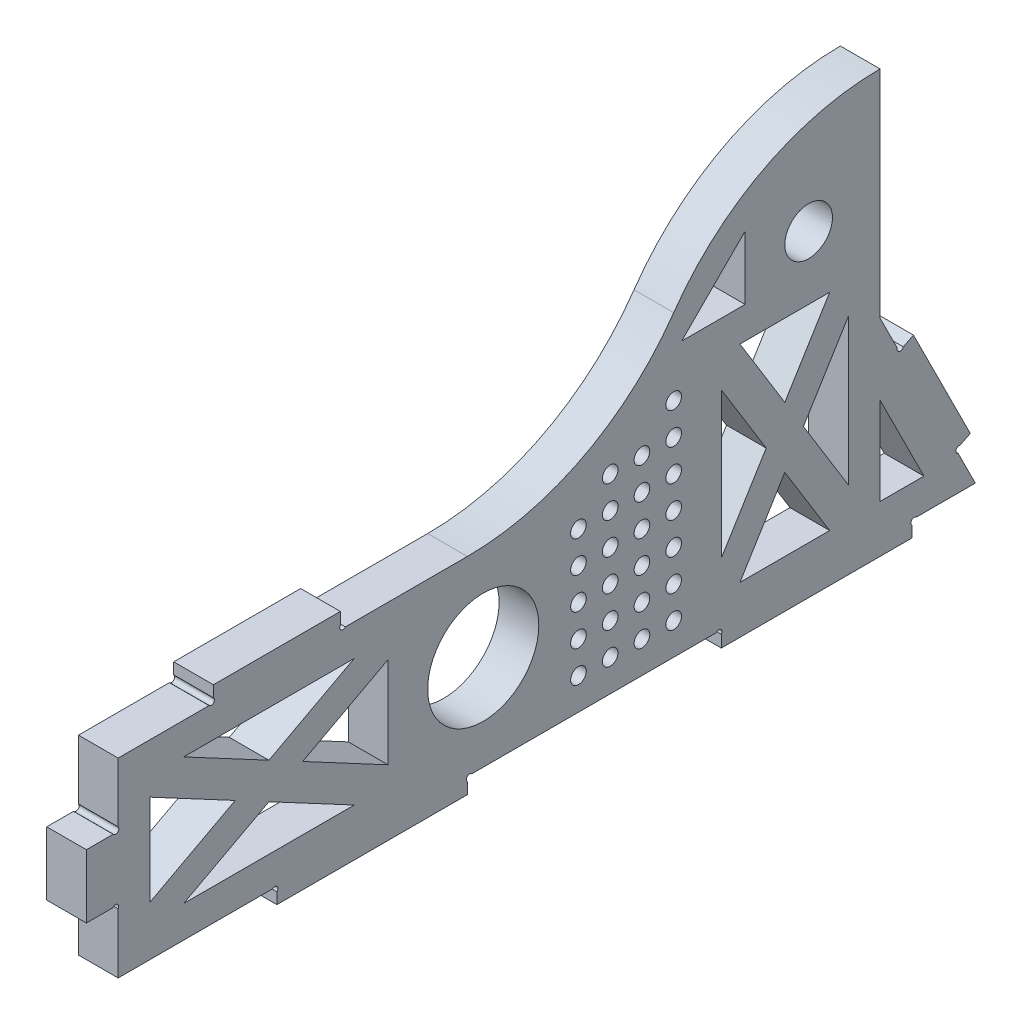
SolidWorks part; units mm, degrees
ref_plane "Front Plane" through (0, 0, 0) normal (0, 0, 1) x (1, 0, 0)
ref_plane "Top Plane" through (0, 0, 0) normal (0, 1, 0) x (1, 0, 0)
ref_plane "Right Plane" through (0, 0, 0) normal (1, 0, 0) x (0, 0, -1)
sketch "Sketch1" plane through (0, 0, 0) normal (1, 0, 0) x (0, 0, -1)
  line L0 (139.7, 38.1) -> (139.7, 124.46)
  line L1 (-177.8, -38.1) -> (177.8, -38.1)
  line L2 (-177.8, -38.1) -> (-177.8, 38.1)
  line L3 (-177.8, 38.1) -> (177.8, 38.1)
  line L4 (177.8, -38.1) -> (177.8, 38.1)
  line L5 (-177.8, -38.1) -> (177.8, 38.1) construction
  line L6 (-177.8, 38.1) -> (177.8, -38.1) construction
  line L7 (139.7, 124.46) -> (-25.4, 38.1)
  line L8 (139.7, 38.1) -> (177.8, -38.1)
  line L9 (-165.1, -38.1) -> (-165.1, 38.1)
  line L11 (-76.2, 38.1) -> (-127, 38.1)
  line L12 (-76.2, 38.1) -> (-76.2, 44.45)
  line L13 (-76.2, 44.45) -> (-127, 44.45)
  line L14 (-127, 38.1) -> (-127, 44.45)
  arc A2 (139.7, 124.46) -> (57.15, 81.28) centre (139.7, 23.9619) ccw
  arc A3 (-25.4, 38.1) -> (57.15, 81.28) centre (-25.4, 138.5981) ccw
  point P0 (0, 0)
  dimension "D6" = 12.7
  dimension "D1" = 50.8
  dimension "D2" = 355.6
  dimension "2" = 76.2
  dimension "D3" = 162.56
  dimension "D4" = 38.1
  dimension "D5" = 152.4
  dimension "D7" = 50.8
  dimension "D8" = 6.35
extrude "Boss-Extrude1" add sketch "Sketch1" along normal blind 15.875
sketch "Sketch2" plane through (15.875, 0, 0) normal (1, 0, 0) x (0, 0, -1)
  line L0 (-165.1, -38.1) -> (177.8, -38.1) construction
  line L1 (139.7, 38.1) -> (139.7, 124.46) construction
  circle A0 centre (111.125, 82.55) radius 9.525
  dimension "D1" = 19.05
  dimension "D2" = 120.65
  dimension "D3" = 28.575
extrude "Cut-Extrude1" cut sketch "Sketch2" against normal through all
sketch "Sketch3" plane through (15.875, 0, 0) normal (1, 0, 0) x (0, 0, -1)
  line L0 (-165.1, -38.1) -> (177.8, -38.1) construction
  line L1 (152.4, -38.1) -> (76.2, -38.1)
  line L2 (152.4, -38.1) -> (152.4, -44.45)
  line L3 (152.4, -44.45) -> (76.2, -44.45)
  line L4 (76.2, -38.1) -> (76.2, -44.45)
  line L5 (-165.1, 38.1) -> (-127, 38.1) construction
  line L6 (-25.4, -38.1) -> (-101.6, -38.1)
  line L7 (-25.4, -38.1) -> (-25.4, -44.45)
  line L8 (-25.4, -44.45) -> (-101.6, -44.45)
  line L9 (-101.6, -38.1) -> (-101.6, -44.45)
  line L10 (-165.1, -38.1) -> (-165.1, 38.1) construction
  line L12 (-165.1, 12.7) -> (-177.8, 12.7)
  line L13 (-165.1, 12.7) -> (-165.1, -12.7)
  line L14 (-165.1, -12.7) -> (-177.8, -12.7)
  line L15 (-177.8, 12.7) -> (-177.8, -12.7)
  dimension "D1" = 6.35
  dimension "D2" = 76.2
  dimension "D3" = 6.35
  dimension "D4" = 76.2
  dimension "D5" = 25.4
  dimension "D6" = 203.2
  dimension "D7" = 12.7
  dimension "D8" = 25.4
  dimension "D9" = 25.4
extrude "Boss-Extrude2" add sketch "Sketch3" against normal blind 15.875
sketch "Sketch9" plane through (15.875, 0, 0) normal (1, 0, 0) x (0, 0, -1)
  line L0 (-25.4, -38.1) -> (76.2, -38.1) construction
  line L1 (-165.1, 12.7) -> (-165.1, 38.1) construction
  circle A0 centre (-19.05, 0) radius 22.225
  dimension "D1" = 44.45
  dimension "D2" = 38.1
  dimension "D3" = 146.05
extrude "Cut-Extrude4" cut sketch "Sketch9" against normal through all
sketch "Sketch10" plane through (15.875, 0, 0) normal (1, 0, 0) x (0, 0, -1)
  line L0 (111.125, 82.55) -> (-19.05, 0) construction
  circle A0 centre (48.1797, 37.897) radius 4
  circle A1 centre (41.3256, 23.4394) radius 4
  circle A2 centre (50.4192, 10.2748) radius 4
  circle A3 centre (66.3668, 11.5678) radius 4
  circle A4 centre (73.2209, 26.0254) radius 4
  circle A5 centre (64.1273, 39.1899) radius 4
  dimension "D1" = 8
extrude "Cut-Extrude5" [suppressed] cut sketch "Sketch10" against normal through all
sketch "Sketch12" plane through (15.875, 0, 0) normal (1, 0, 0) x (0, 0, -1)
  line L0 (157.251, -25.4) -> (139.7, 9.7019)
  line L1 (139.7, 9.7019) -> (139.7, -25.4)
  line L2 (139.7, -25.4) -> (157.251, -25.4)
  line L3 (139.7, 38.1) -> (177.8, -38.1) construction
  line L4 (152.4, -38.1) -> (177.8, -38.1) construction
  line L5 (139.7, 38.1) -> (139.7, 124.46) construction
  line L6 (132.408, -22.072) -> (81.608, 60.478)
  line L7 (127, 57.15) -> (76.2, 57.15)
  line L8 (127, 57.15) -> (127, -25.4)
  line L9 (127, -25.4) -> (76.2, -25.4)
  line L10 (76.2, 57.15) -> (76.2, -25.4)
  line L11 (127, 57.15) -> (76.2, -25.4) construction
  line L12 (127, -25.4) -> (76.2, 57.15) construction
  line L13 (121.592, 60.478) -> (70.792, -22.072)
  line L14 (121.592, -28.728) -> (70.792, 53.822)
  line L15 (132.408, 53.822) -> (81.608, -28.728)
  line L16 (101.6, -25.4) -> (101.6, 57.15) construction
  line L20 (-165.1, -38.1) -> (-165.1, -12.7) construction
  line L21 (-57.15, 25.4) -> (-152.4, 25.4)
  line L22 (-57.15, 25.4) -> (-57.15, -25.4)
  line L23 (-57.15, -25.4) -> (-152.4, -25.4)
  line L24 (-152.4, 25.4) -> (-152.4, -25.4)
  line L25 (-57.15, 25.4) -> (-152.4, -25.4) construction
  line L26 (-57.15, -25.4) -> (-152.4, 25.4) construction
  line L27 (-165.1, -38.1) -> (-101.6, -38.1) construction
  line L28 (-60.1382, 31.0029) -> (-155.3882, -19.7971)
  line L29 (-54.1618, -19.7971) -> (-149.4118, 31.0029)
  line L30 (-54.1618, 19.7971) -> (-149.4118, -31.0029)
  line L31 (-60.1382, -31.0029) -> (-155.3882, 19.7971)
  circle A0 centre (111.125, 82.55) radius 9.525 construction
  point P9 (101.6, 15.875)
  point P26 (-104.775, 0)
  dimension "D1" = 12.7
  dimension "D2" = 12.7
  dimension "D3" = 25.4
  dimension "D4" = 12.7
  dimension "D5" = 50.8
  dimension "D8" = 50.8
  dimension "D9" = 95.25
  dimension "D10" = 12.7
  dimension "D11" = 12.7
  dimension "D6" = 6.35
  dimension "D7" = 6.35
  dimension "D12" = 6.35
  dimension "D13" = 6.35
extrude "Cut-Extrude6" cut sketch "Sketch12" against normal through all contours L1 L2 L0 | L8 L15 L6 | L14 L15 L9 | L13 L14 L10 | L13 L7 L6 | L22 L30 L29 | L23 L31 L30 | L28 L31 L24 | L29 L28 L21
sketch "Sketch13" plane through (15.875, 0, 0) normal (1, 0, 0) x (0, 0, -1)
  line L0 (-25.4, -38.1) -> (76.2, -38.1) construction
  circle A1 centre (31.75, -25.4) radius 3.127
  circle A2 centre (19.05, -25.4) radius 3.127
  circle A16 centre (44.45, -25.4) radius 3.127
  circle A29 centre (57.15, -25.4) radius 3.127
  circle A43 centre (31.75, -6.35) radius 3.127 [skipped]
  circle A44 centre (44.45, -6.35) radius 3.127 [skipped]
  circle A45 centre (57.15, -6.35) radius 3.127 [skipped]
  circle A46 centre (31.75, 12.7) radius 3.127 [skipped]
  circle A47 centre (44.45, 12.7) radius 3.127 [skipped]
  circle A48 centre (57.15, 12.7) radius 3.127 [skipped]
  circle A49 centre (31.75, 31.75) radius 3.127 [skipped]
  circle A50 centre (44.45, 31.75) radius 3.127 [skipped]
  circle A51 centre (57.15, 31.75) radius 3.127 [skipped]
  circle A52 centre (19.05, -6.35) radius 3.127 [skipped]
  circle A53 centre (19.05, 12.7) radius 3.127 [skipped]
  circle A54 centre (19.05, 31.75) radius 3.127 [skipped]
  circle A55 centre (19.05, -12.7) radius 3.127
  circle A56 centre (31.75, -12.7) radius 3.127
  circle A57 centre (44.45, -12.7) radius 3.127
  circle A58 centre (57.15, -12.7) radius 3.127
  circle A59 centre (19.05, 0) radius 3.127
  circle A60 centre (31.75, 0) radius 3.127
  circle A61 centre (44.45, 0) radius 3.127
  circle A62 centre (57.15, 0) radius 3.127
  circle A63 centre (19.05, 12.7) radius 3.127
  circle A64 centre (31.75, 12.7) radius 3.127
  circle A65 centre (44.45, 12.7) radius 3.127
  circle A66 centre (57.15, 12.7) radius 3.127
  circle A67 centre (19.05, 25.4) radius 3.127
  circle A68 centre (31.75, 25.4) radius 3.127
  circle A69 centre (44.45, 25.4) radius 3.127
  circle A70 centre (57.15, 25.4) radius 3.127
  circle A71 centre (31.75, 38.1) radius 3.127
  circle A72 centre (44.45, 38.1) radius 3.127
  circle A73 centre (57.15, 38.1) radius 3.127
  circle A75 centre (57.15, 50.8) radius 3.127
  circle A76 centre (44.45, 50.8) radius 3.127 [skipped]
  dimension "D1" = 6.254
  dimension "D3" = 38.1
  dimension "D2" = 12.7
  dimension "D5" = 4
  dimension "D4" = 4
  dimension "D6" = 5
  dimension "D7" = 2
  dimension "D8" = 2
sketch "Sketch14" plane through (15.875, 0, 0) normal (1, 0, 0) x (0, 0, -1)
  line L0 (147.3908, 22.7185) -> (170.1092, -22.7185)
  line L1 (147.3908, 22.7185) -> (153.0704, 25.5583)
  line L2 (170.1092, -22.7185) -> (175.7888, -19.8786)
  line L3 (153.0704, 25.5583) -> (175.7888, -19.8786)
  line L4 (139.7, 38.1) -> (177.8, -38.1) construction
  line L5 (158.75, 0) -> (192.2502, 16.7501) construction
  dimension "D1" = 6.35
  dimension "D2" = 50.8
extrude "Boss-Extrude3" add sketch "Sketch14" against normal blind 15.875
sketch "Sketch15" plane through (15.875, 0, 0) normal (1, 0, 0) x (0, 0, -1)
  line L0 (170.1092, -22.7185) -> (170.453, -22.833) construction
  line L1 (170.1092, -22.7185) -> (177.8, -38.1) construction
  line L2 (170.1092, -22.7185) -> (175.7888, -19.8786) construction
  line L3 (147.3908, 22.7185) -> (149.5267, 29.1262) construction
  line L4 (153.0704, 25.5583) -> (147.3908, 22.7185) construction
  circle A0 centre (-166.1476, -13.4179) radius 1.27
  circle A2 centre (-127.8675, 39.0275) radius 1.27
  circle A4 centre (-102.4687, -39.0264) radius 1.27
  circle A6 centre (75.2028, -38.8864) radius 1.27
  circle A8 centre (153.2761, -39.0194) radius 1.27
  circle A9 centre (-24.5016, -38.9977) radius 1.27
  circle A10 centre (-166.0964, 13.4875) radius 1.27
  circle A11 centre (-75.2053, 38.8897) radius 1.27
  circle A14 centre (171.3141, -23.1201) radius 1.27
  circle A15 centre (147.7924, 23.9233) radius 1.27
  dimension "D1" = 45
  dimension "D2" = 2.54
  dimension "D3" = 45
extrude "Cut-Extrude8" cut sketch "Sketch15" against normal through all
extrude "Cut-Extrude9" cut sketch "Sketch13" against normal through all
sketch "Sketch17" plane through (15.875, 0, 0) normal (1, 0, 0) x (0, 0, -1)
  line L0 (60.325, 69.85) -> (85.725, 69.85)
  line L1 (85.725, 69.85) -> (85.725, 95.25)
  line L2 (85.725, 95.25) -> (60.325, 69.85)
  line L3 (119.544, 57.15) -> (83.656, 57.15) construction
  circle A0 centre (111.125, 82.55) radius 9.525 construction
  dimension "D1" = 25.4
  dimension "D2" = 25.4
  dimension "D3" = 25.4
  dimension "D4" = 12.7
extrude "Cut-Extrude10" cut sketch "Sketch17" against normal through all
